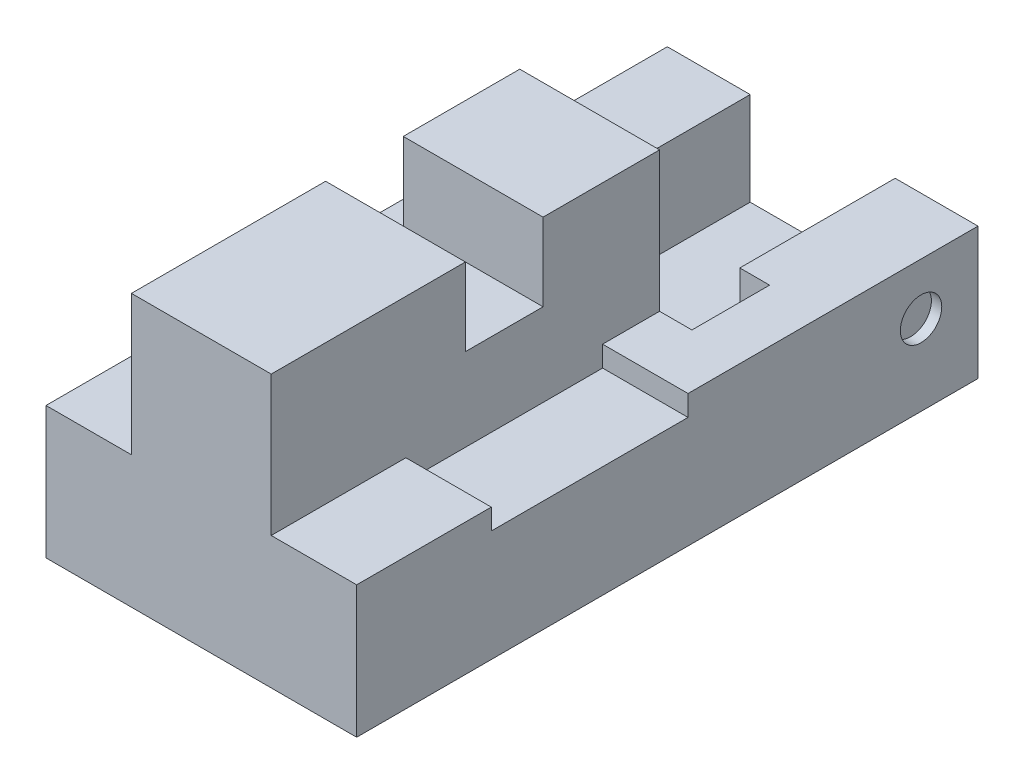
SolidWorks part; units mm, degrees
ref_plane "Front Plane" through (0, 0, 0) normal (0, 0, 1) x (1, 0, 0)
ref_plane "Top Plane" through (0, 0, 0) normal (0, 1, 0) x (1, 0, 0)
ref_plane "Right Plane" through (0, 0, 0) normal (1, 0, 0) x (0, 0, -1)
sketch "Sketch1" plane through (0, 0, 0) normal (0, 1, 0) x (1, 0, 0)
  line L0 (-1.4, 3) -> (-1.4, 0)
  line L1 (-1.4, 0) -> (-1.975, 0)
  line L2 (-1.975, 0) -> (-1.975, -1.5)
  line L4 (-3, -9) -> (-3, 3)
  line L5 (-3, 3) -> (-1.4, 3)
  line L6 (1.4, 0) -> (1.4, 3)
  line L7 (1.4, 3) -> (3, 3)
  line L8 (3, 3) -> (3, -9)
  line L10 (1.975, -1.5) -> (1.975, 0)
  line L11 (1.975, 0) -> (1.4, 0)
  line L12 (-1.4, 0) -> (1.4, 0) construction
  line L13 (-1.975, -1.5) -> (1.975, -1.5)
  line L14 (-3, -9) -> (3, -9)
  circle A0 centre (0, -5) radius 1.8126 construction
  dimension "D1" = 2.8
  dimension "D2" = 3.95
  dimension "D3" = 3
  dimension "D4" = 5
  dimension "D5" = 6
  dimension "D6" = 1.5
  dimension "D7" = 9
extrude "Boss-Extrude1" add sketch "Sketch1" along normal blind 1.8
sketch "Sketch2" plane through (0, 0, 0) normal (0, -1, 0) x (1, 0, 0)
  line L0 (-3, 9) -> (3, 9) construction
  line L1 (-3, 9) -> (3, 9)
  line L2 (-3, -3) -> (-3, 9) construction
  line L3 (-3, -3) -> (-3, 9)
  line L4 (3, 9) -> (3, -3) construction
  line L5 (3, 9) -> (3, -3)
  line L6 (-3, -3) -> (3, -3)
extrude "Boss-Extrude2" add sketch "Sketch2" along normal blind 0.75
sketch "Sketch7" plane through (0, 1.8, 0) normal (0, 1, 0) x (1, 0, 0)
  line L0 (-3, 3) -> (-3, -9) construction
  line L1 (-1.35, -2.6) -> (-3, -2.6)
  line L2 (-1.35, -2.6) -> (-1.35, -6.4)
  line L3 (-1.35, -6.4) -> (-3, -6.4)
  line L4 (-3, -2.6) -> (-3, -6.4)
  line L5 (3, -9) -> (3, 3) construction
  line L6 (1.35, -6.4) -> (3, -6.4)
  line L7 (1.35, -6.4) -> (1.35, -2.6)
  line L8 (1.35, -2.6) -> (3, -2.6)
  line L9 (3, -6.4) -> (3, -2.6)
  line L10 (1.35, -2.6) -> (-1.35, -2.6) construction
extrude "Cut-Extrude2" cut sketch "Sketch7" against normal blind 0.4
sketch "Sketch9" plane through (3, 0, 0) normal (1, 0, 0) x (0, 0, -1)
  line L0 (-2.6, 1.8) -> (3, 1.8) construction
  line L1 (3, 1.8) -> (3, -0.75) construction
  circle A0 centre (1.9, 0.8) radius 0.4
  dimension "D1" = 0.8
  dimension "D2" = 1
  dimension "D3" = 1.1
extrude "Cut-Extrude4" cut sketch "Sketch9" against normal blind 0.2
mirror "Mirror1" about plane through (0, 0, 0) normal (1, 0, 0) of "Cut-Extrude4"
sketch "Sketch10" plane through (0, 1.8, 0) normal (0, 1, 0) x (1, 0, 0)
  line L2 (-1.35, -6.4) -> (-1.35, -9)
  line L3 (1.35, -6.4) -> (1.35, -9)
  line L4 (-1.35, -2.6) -> (-1.35, -1.5)
  line L5 (1.35, -2.6) -> (1.35, -1.5)
  line L20 (-1.35, -2.6) -> (-1.35, -6.4)
  line L21 (-1.35, -6.4) -> (-3, -6.4)
  line L22 (-3, -6.4) -> (-3, -9)
  line L23 (-3, -9) -> (3, -9)
  line L24 (3, -9) -> (3, -6.4)
  line L25 (3, -6.4) -> (1.35, -6.4)
  line L26 (1.35, -6.4) -> (1.35, -2.6)
  line L27 (1.35, -2.6) -> (3, -2.6)
  line L28 (3, -2.6) -> (3, 3)
  line L29 (3, 3) -> (1.4, 3)
  line L30 (1.4, 3) -> (1.4, 0)
  line L31 (1.4, 0) -> (1.975, 0)
  line L32 (1.975, 0) -> (1.975, -1.5)
  line L33 (1.975, -1.5) -> (-1.975, -1.5)
  line L34 (-1.975, -1.5) -> (-1.975, 0)
  line L35 (-1.975, 0) -> (-1.4, 0)
  line L36 (-1.4, 0) -> (-1.4, 3)
  line L37 (-1.4, 3) -> (-3, 3)
  line L38 (-3, 3) -> (-3, -2.6)
  line L39 (-3, -2.6) -> (-1.35, -2.6)
  line L40 (-1.35, -2.6) -> (-1.35, -6.4)
  line L43 (-1.35, -9) -> (1.35, -9)
  line L46 (1.35, -6.4) -> (1.35, -2.6)
  line L53 (1.35, -1.5) -> (-1.35, -1.5)
  dimension "D1" = 0
extrude "Boss-Extrude3" add sketch "Sketch10" along normal blind 2.7
sketch "Sketch11" plane through (0, 4.5, 0) normal (0, 1, 0) x (1, 0, 0)
  line L0 (-1.35, -1.5) -> (-1.35, -9) construction
  line L1 (-1.35, -3.75) -> (1.35, -3.75)
  line L2 (-1.35, -3.75) -> (-1.35, -5.25)
  line L3 (-1.35, -5.25) -> (1.35, -5.25)
  line L4 (1.35, -3.75) -> (1.35, -5.25)
  line L5 (1.35, -9) -> (1.35, -1.5) construction
  line L6 (-1.35, -2.6) -> (1.35, -6.4) construction
  line L7 (-1.35, -3.75) -> (1.35, -5.25) construction
  point P12 (0, -4.5)
  point P13 (0, 0)
  dimension "D1" = 1.5
extrude "Cut-Extrude5" cut sketch "Sketch11" against normal offset from surface (1.5 mm away) 1.6 up to face at (-2.175, 1.4, 4.5)
